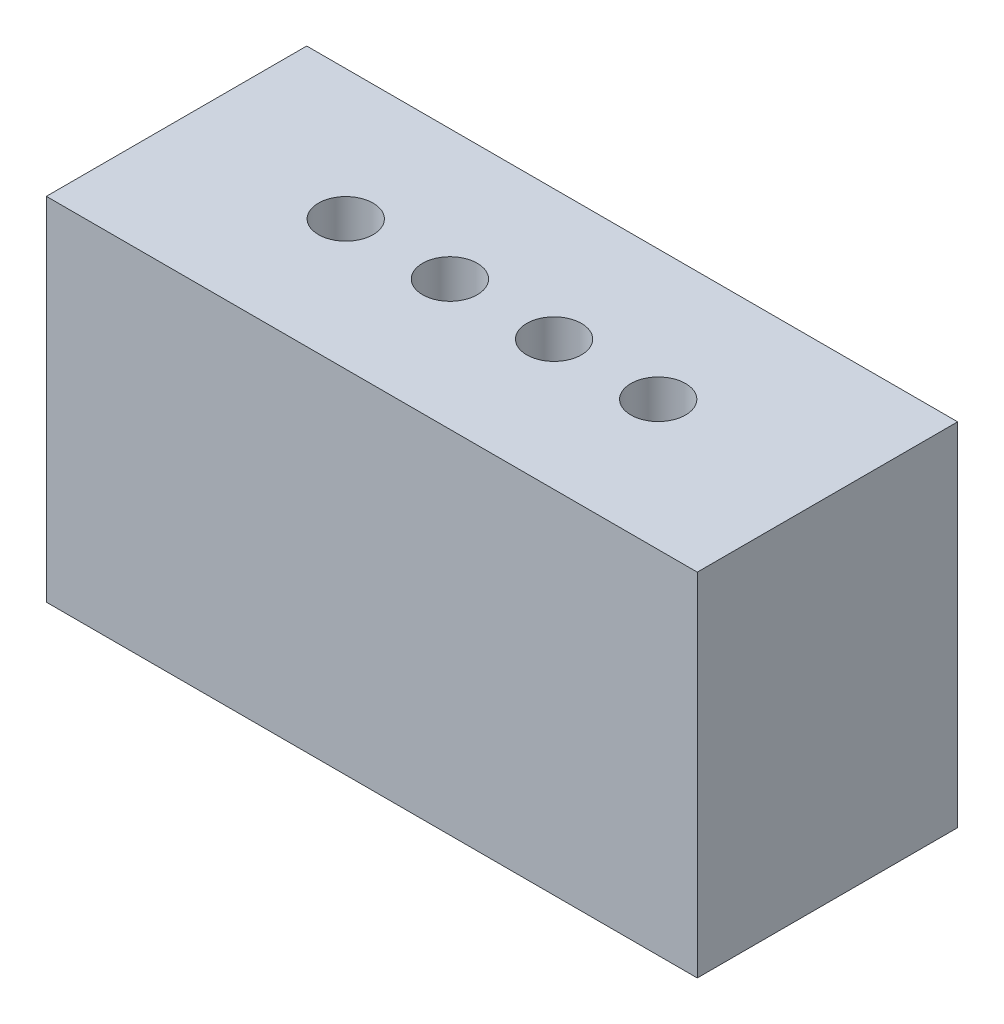
SolidWorks part; units mm, degrees
ref_plane "Ebene vorne" through (0, 0, 0) normal (0, 0, 1) x (1, 0, 0)
ref_plane "Ebene oben" through (0, 0, 0) normal (0, 1, 0) x (1, 0, 0)
ref_plane "Ebene rechts" through (0, 0, 0) normal (1, 0, 0) x (0, 0, -1)
sketch "Skizze1" plane through (0, 0, 0) normal (0, 1, 0) x (1, 0, 0)
  line L1 (0, 0) -> (50, 0)
  line L2 (0, 0) -> (0, 20)
  line L3 (0, 20) -> (50, 20)
  line L4 (50, 0) -> (50, 20)
  dimension "D1" = 50
  dimension "D2" = 20
extrude "Aufsatz-Linear austragen1" add sketch "Skizze1" along normal blind 27
hole_wizard "Ø4.2 (4.2) Durchmesser Bohrung1" positions "Skizze2" profile "Skizze3" hole size "Ø4.2" standard "DIN" end condition up to next
sketch "Skizze2" plane through (0, 27, 0) normal (0, 1, 0) x (1, 0, 0)
  line L0 (0, 10) -> (50, 10) construction
  line L1 (0, 20) -> (0, 0) construction
  line L2 (50, 0) -> (50, 20) construction
  point P7 (13, 10)
  point P11 (21, 10)
  point P12 (29, 10)
  point P13 (37, 10)
  dimension "D1" = 13
  dimension "D2" = 4
sketch "Skizze3" plane through (37, 27, -10) normal (1, 0, 0) x (0, 0, 1)
  line L0 (0, 0) -> (0, 27)
  line L1 (0, 27) -> (2.1, 27)
  line L2 (2.1, 27) -> (2.1, 0)
  line L5 (2.1, 0) -> (0, 0)
  line L11 (0, -6.35) -> (0, 107.95) construction
  dimension "Bohrerdurchmesser" = 4.2
  dimension "Bohrungstiefe" = 27
